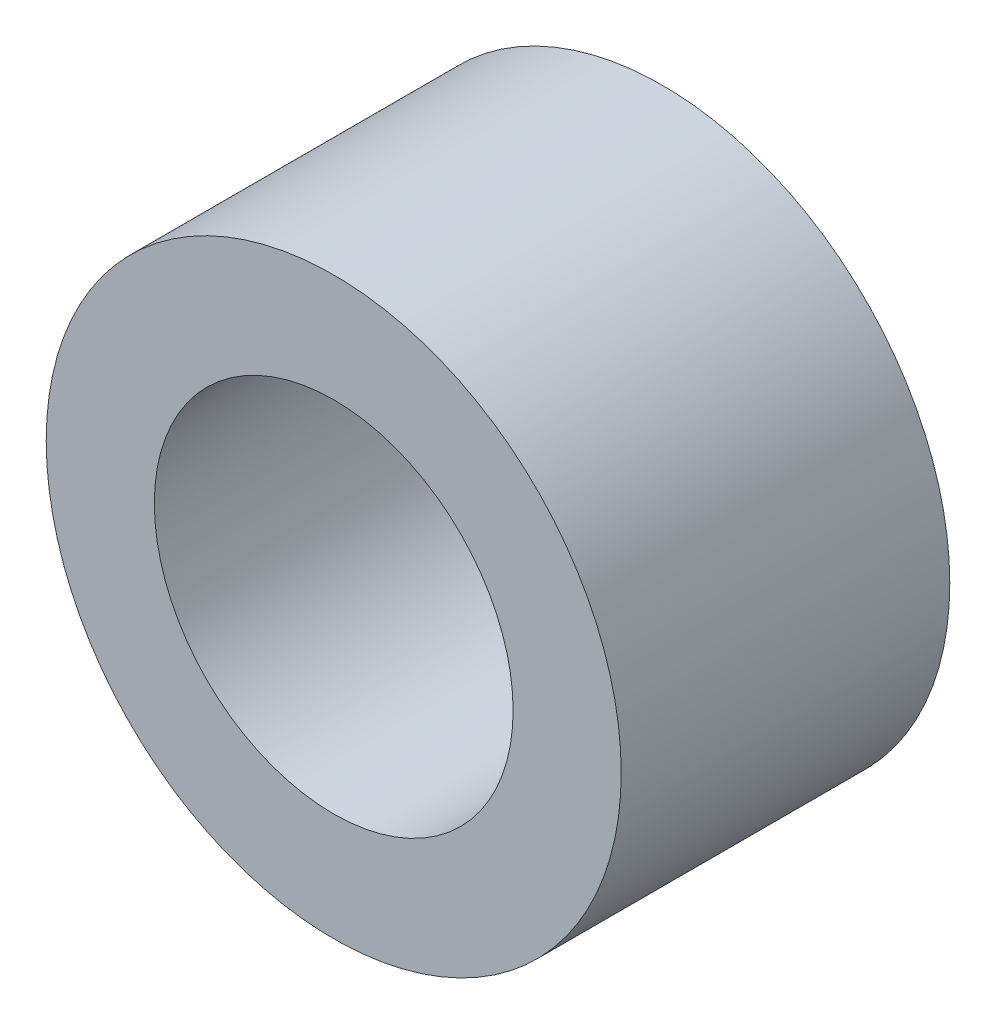
SolidWorks part; units mm, degrees
material "PVC Rigid"
ref_plane "Front" through (0, 0, 0) normal (0, 0, 1) x (1, 0, 0)
ref_plane "Top" through (0, 0, 0) normal (0, 1, 0) x (1, 0, 0)
ref_plane "Right" through (0, 0, 0) normal (1, 0, 0) x (0, 0, -1)
sketch "Sketch1" plane through (0, 0, 0) normal (0, 0, 1) x (1, 0, 0)
  circle A0 centre (0, 0) radius 6.9342
  circle A1 centre (0, 0) radius 11.1125
  dimension "D1" = 22.225
  dimension "D2" = 13.8684
extrude "Boss-Extrude1" add sketch "Sketch1" along normal blind 12.7
